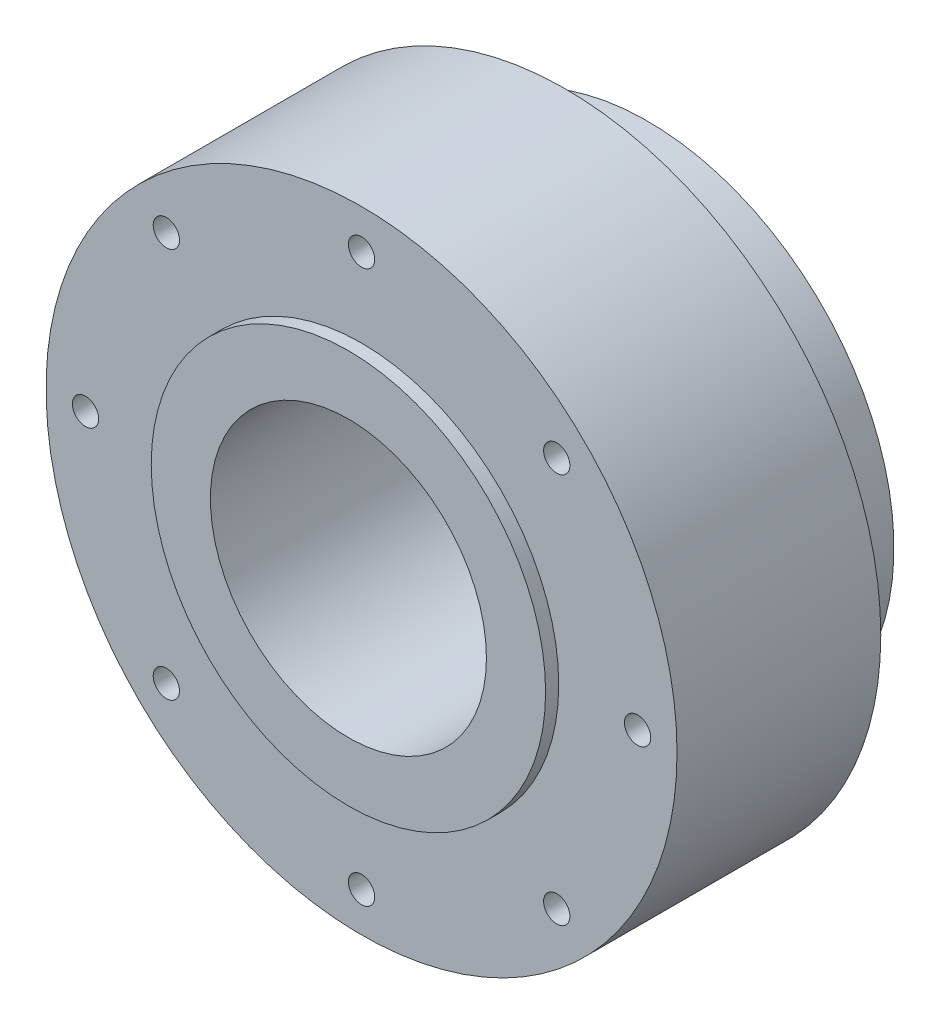
SolidWorks part; units mm, degrees
ref_plane "Front Plane" through (0, 0, 0) normal (0, 0, 1) x (1, 0, 0)
ref_plane "Top Plane" through (0, 0, 0) normal (0, 1, 0) x (1, 0, 0)
ref_plane "Right Plane" through (0, 0, 0) normal (1, 0, 0) x (0, 0, -1)
sketch "Sketch2" plane through (0, 0, 0) normal (1, 0, 0) x (0, 0, -1)
  line L0 (0, 0) -> (100.9689, 0) construction
  point P1 (0, 0)
sketch "Sketch3" plane through (0, 0, 0) normal (0, 0, 1) x (1, 0, 0)
  circle A0 centre (0, 0) radius 48
  dimension "D1" = 96
extrude "Boss-Extrude1" add sketch "Sketch3" along normal blind 31
sketch "Sketch4" plane through (0, 0, 31) normal (0, 0, 1) x (1, 0, 0)
  line L0 (0, -42) -> (0, 42) construction
  circle A0 centre (0, 0) radius 42 construction
  circle A1 centre (0, 42) radius 2
  circle A2 centre (29.6985, 29.6985) radius 2
  circle A3 centre (42, 0) radius 2
  circle A4 centre (29.6985, -29.6985) radius 2
  circle A5 centre (0, -42) radius 2
  circle A6 centre (-29.6985, -29.6985) radius 2
  circle A7 centre (-42, 0) radius 2
  circle A8 centre (-29.6985, 29.6985) radius 2
  point P6 (0, 42)
  point P8 (29.6985, 29.6985)
  point P9 (42, 0)
  point P10 (29.6985, -29.6985)
  point P11 (0, -42)
  point P12 (-29.6985, -29.6985)
  point P13 (-42, 0)
  point P14 (-29.6985, 29.6985)
  point P15 (0, 0)
  point P31 (0, 0)
  dimension "D1" = 84
  dimension "D3" = 4
  dimension "D2" = 8
  dimension "D4" = 8
extrude "Cut-Extrude1" cut sketch "Sketch4" against normal blind 3.5
sketch "Sketch5" plane through (0, 0, 31) normal (0, 0, 1) x (1, 0, 0)
  circle A0 centre (0, 0) radius 30
  dimension "D1" = 60
extrude "Boss-Extrude2" add sketch "Sketch5" along normal blind 2
sketch "Sketch6" plane through (0, 0, 33) normal (0, 0, 1) x (1, 0, 0)
  circle A0 centre (0, 0) radius 21
  dimension "D1" = 42
sketch "Sketch7" plane through (0, 0, 0) normal (0, 0, -1) x (-1, 0, 0)
  circle A0 centre (0, 0) radius 37.5
  dimension "D1" = 75
extrude "Boss-Extrude3" add sketch "Sketch7" along normal blind 12.5
extrude "Cut-Extrude3" cut sketch "Sketch6" against normal blind 33 contours A0
sketch "Sketch8" plane through (0, 0, 0) normal (0, 0, -1) x (-1, 0, 0)
  circle A0 centre (0, 0) radius 42 construction
  circle A1 centre (0, 42) radius 2
  circle A2 centre (29.6985, 29.6985) radius 2
  circle A3 centre (42, 0) radius 2
  circle A4 centre (29.6985, -29.6985) radius 2
  circle A5 centre (0, -42) radius 2
  circle A6 centre (-29.6985, -29.6985) radius 2
  circle A7 centre (-42, 0) radius 2
  circle A8 centre (-29.6985, 29.6985) radius 2
  point P3 (0, 42)
  point P22 (0, 0)
  dimension "D1" = 84
  dimension "D2" = 4
  dimension "D3" = 8
extrude "Cut-Extrude4" cut sketch "Sketch8" against normal blind 3.5
